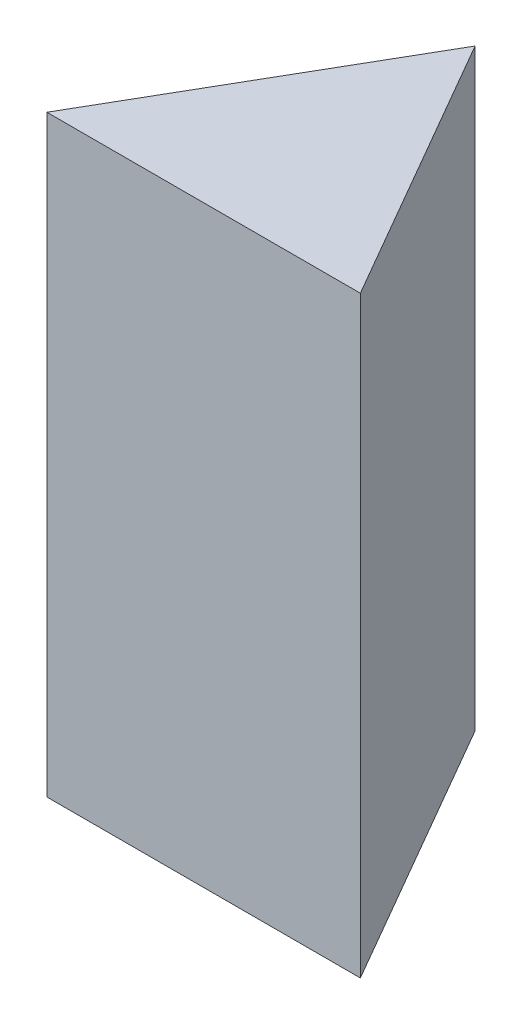
SolidWorks part; units mm, degrees
ref_plane "前视基准面" through (0, 0, 0) normal (0, 0, 1) x (1, 0, 0)
ref_plane "上视基准面" through (0, 0, 0) normal (0, 1, 0) x (1, 0, 0)
ref_plane "右视基准面" through (0, 0, 0) normal (1, 0, 0) x (0, 0, -1)
other "Configuration Table"
sketch "草图1" plane through (25.6973, -344.6009, 0) normal (0, 1, 0) x (1, 0, 0)
  line L0 (-3.529, 18.1847) -> (-22.029, -13.8582)
  line L1 (-22.029, -13.8582) -> (14.971, -13.8582)
  line L2 (14.971, -13.8582) -> (-3.529, 18.1847)
  dimension "D1" = 37
  dimension "D2" = 37
  dimension "D3" = 37
extrude "凸台-拉伸1" add sketch "草图1" along normal blind 70
sketch "草图2" plane through (0, -274.6009, 0) normal (0, 1, 0) x (1, 0, 0)
  circle A0 centre (22.1683, -3.1772) radius 10.681
